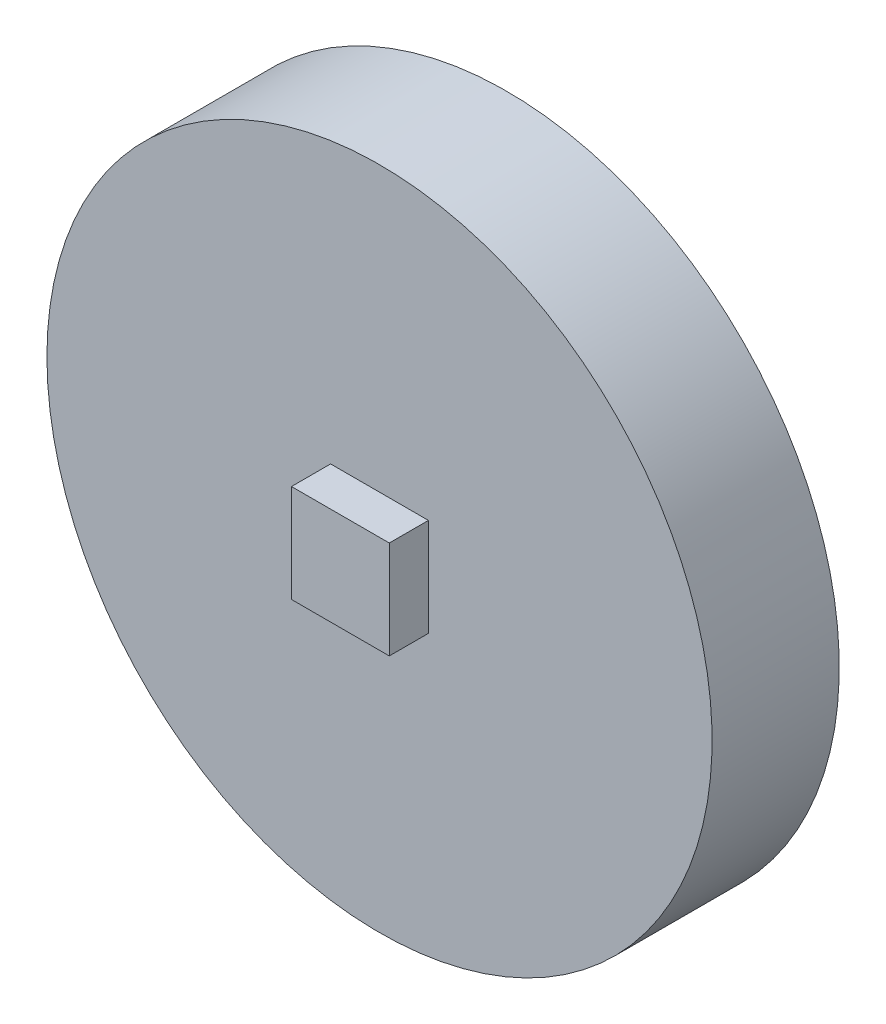
SolidWorks part; units mm, degrees
ref_plane "Front Plane" through (0, 0, 0) normal (0, 0, 1) x (1, 0, 0)
ref_plane "Top Plane" through (0, 0, 0) normal (0, 1, 0) x (1, 0, 0)
ref_plane "Right Plane" through (0, 0, 0) normal (1, 0, 0) x (0, 0, -1)
sketch "Sketch1" plane through (0, 0, 0) normal (0, 0, 1) x (1, 0, 0)
  circle A0 centre (0, 0) radius 17
  dimension "D1" = 34
extrude "Boss-Extrude1" add sketch "Sketch1" along normal blind 6.5
sketch "Sketch2" plane through (0, 0, 6.5) normal (0, 0, 1) x (1, 0, 0)
  line L1 (2.5, 2.5) -> (-2.5, 2.5)
  line L2 (2.5, 2.5) -> (2.5, -2.5)
  line L3 (2.5, -2.5) -> (-2.5, -2.5)
  line L4 (-2.5, 2.5) -> (-2.5, -2.5)
  line L5 (2.5, 2.5) -> (-2.5, -2.5) construction
  line L6 (2.5, -2.5) -> (-2.5, 2.5) construction
  point P0 (0, 0)
  dimension "D1" = 5
  dimension "D2" = 5
extrude "Boss-Extrude2" add sketch "Sketch2" along normal blind 2
